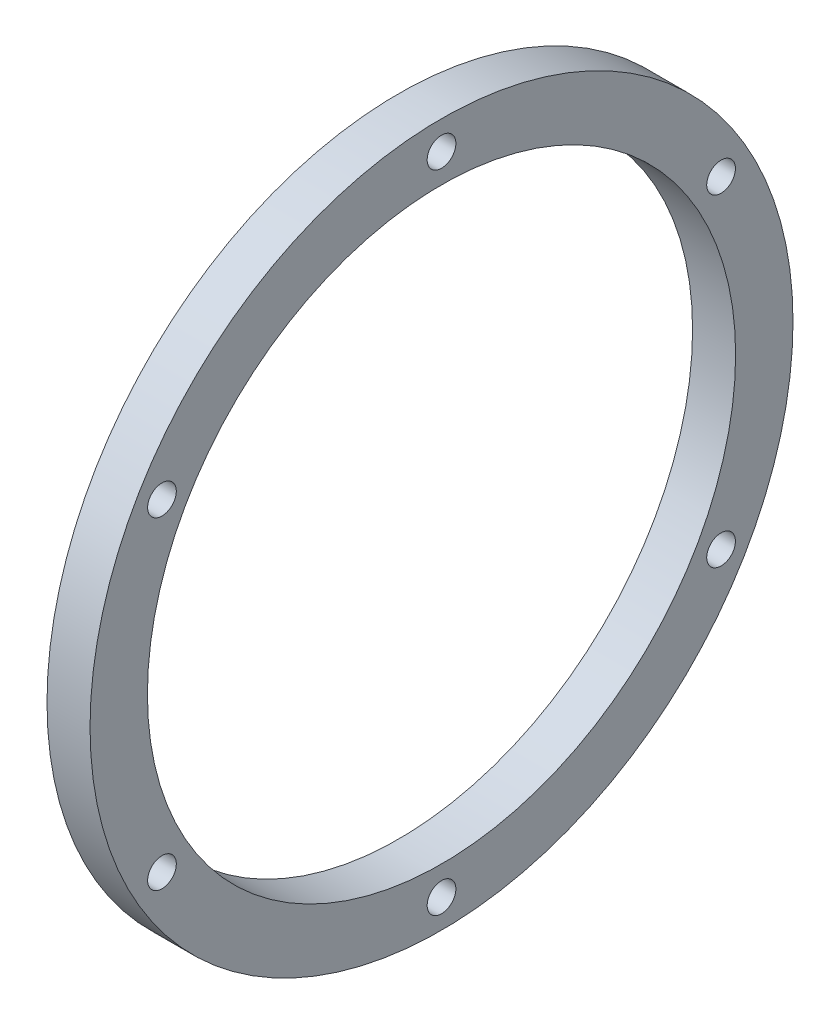
SolidWorks part; units mm, degrees
material "1060 Alloy"
ref_plane "Front Plane" through (0, 0, 0) normal (0, 0, 1) x (1, 0, 0)
ref_plane "Top Plane" through (0, 0, 0) normal (0, 1, 0) x (1, 0, 0)
ref_plane "Right Plane" through (0, 0, 0) normal (1, 0, 0) x (0, 0, -1)
sketch "Sketch1" plane through (0, 0, 0) normal (1, 0, 0) x (0, 0, -1)
  circle A0 centre (0, 0) radius 49
  circle A1 centre (0, 0) radius 41
extrude "Boss-Extrude1" add sketch "Sketch1" along normal blind 6
hole_wizard "Ø4.0mm Dowel Hole1" positions "Sketch2" profile "Sketch3" hole size "Ø4.0" standard "ISO"
sketch "Sketch2" plane through (6, 0, 0) normal (1, 0, 0) x (0, 0, -1)
  line L0 (0, 44.2539) -> (0, -44.2539) construction
  line L1 (55, 0) -> (-55, 0) construction
  point P0 (0, 45)
  dimension "D1" = 45
sketch "Sketch3" plane through (6, 45, 0) normal (0, 1, 0) x (0, 0, -1)
  line L0 (0, 0) -> (0, 51.2017)
  line L1 (0, 51.2017) -> (2, 50)
  line L2 (2, 50) -> (2, 0)
  line L5 (2, 0) -> (0, 0)
  line L10 (0, 51.2017) -> (-2, 50) construction
  line L11 (0, -6.35) -> (0, 107.95) construction
  dimension "Hole Dia." = 4
  dimension "Hole Depth" = 50
  dimension "Drill Angle" = 118
pattern_circular "CirPattern1" count 6 over 360 about axis through (0, 0, 0) along (1, 0, 0) of "Ø4.0mm Dowel Hole1"
